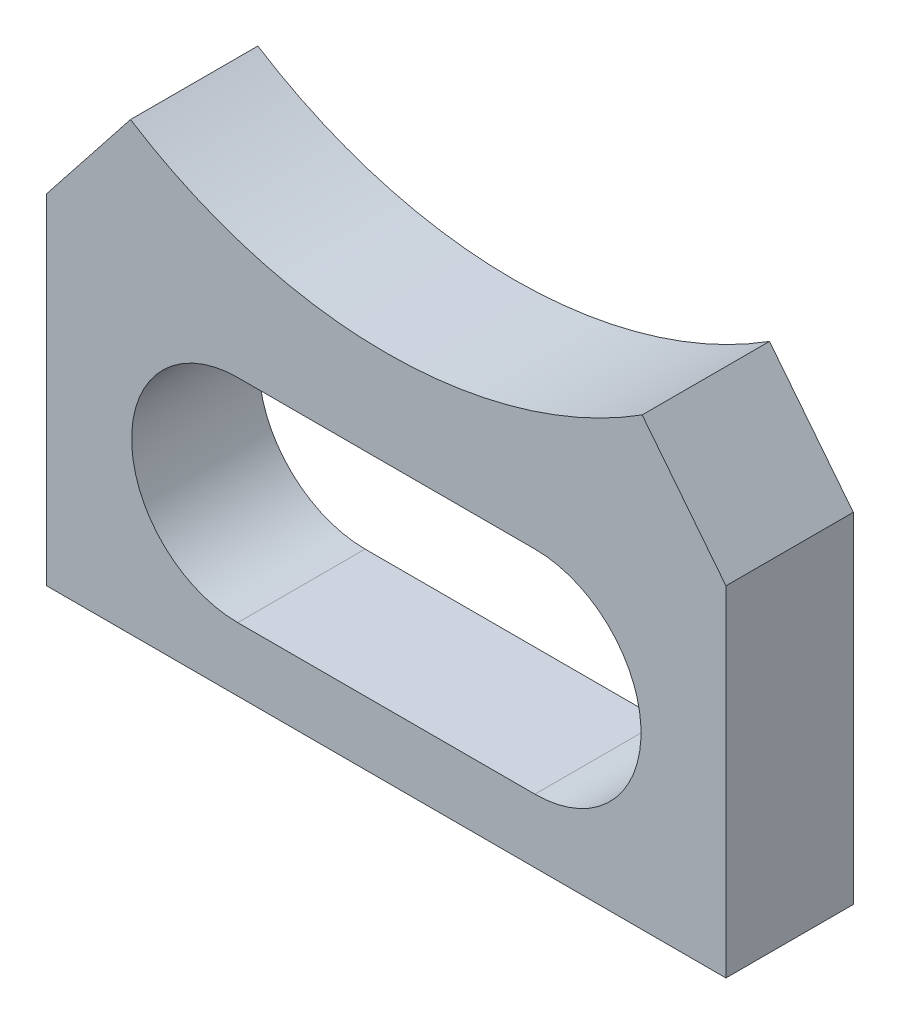
SolidWorks part; units mm, degrees
ref_plane "Plan de face" through (0, 0, 0) normal (0, 0, 1) x (1, 0, 0)
ref_plane "Plan de dessus" through (0, 0, 0) normal (0, 1, 0) x (1, 0, 0)
ref_plane "Plan de droite" through (0, 0, 0) normal (1, 0, 0) x (0, 0, -1)
sketch "Esquisse1" plane through (0, 0, 0) normal (0, 0, 1) x (1, 0, 0)
  line L0 (-16, 0) -> (16, 0)
  line L1 (-16, 0) -> (-16, 16)
  line L2 (0, 21) -> (12.052, 21) construction
  line L3 (16, 16) -> (16, 0)
  line L4 (-16, 16) -> (-12.052, 21)
  line L6 (-12.052, 21) -> (-16, 21) construction
  line L7 (12.052, 21) -> (16, 21) construction
  line L8 (0, 74.4173) -> (0, 62.5) construction
  line L10 (16, 16) -> (12.052, 21)
  line L11 (0, 62.5) -> (0, 21) construction
  line L12 (0, 21) -> (0, -33.4261) construction
  line L13 (-12.052, 21) -> (0, 21) construction
  line L14 (-7, 8) -> (7, 8) construction
  line L15 (-7, 13) -> (7, 13)
  line L16 (-7, 3) -> (7, 3)
  arc A0 (-12.052, 21) -> (12.052, 21) centre (0, 40) ccw
  arc A1 (0, 62.5) -> (-12.052, 21) centre (0, 40) ccw construction
  arc A2 (12.052, 21) -> (0, 62.5) centre (0, 40) ccw construction
  arc A3 (-7, 13) -> (-7, 3) centre (-7, 8) ccw
  arc A4 (7, 3) -> (7, 13) centre (7, 8) ccw
  point P14 (0, 17.5)
  point P17 (0, 8)
  dimension "D2" = 45
  dimension "D8" = 5
  dimension "D1" = 32
  dimension "D3" = 16
  dimension "D4" = 21
  dimension "D5" = 17.5
  dimension "D6" = 9
  dimension "D7" = 8
extrude "Boss.-Extru.2" add sketch "Esquisse1" against normal blind 6
sketch "Esquisse2" plane through (16, 0, 0) normal (1, 0, 0) x (0, 0, -1)
  line L0 (6, 16) -> (0, 16) construction
  line L1 (0, 0) -> (0, 16) construction
  circle A0 centre (3, 11) radius 0.8
  circle A1 centre (3, 4) radius 0.8
  point P7 (0, 0)
  point P10 (3, 11)
  point P11 (3, 4)
  point P12 (0, 0)
  dimension "D4" = 1.6
  dimension "D5" = 1.6
  dimension "D1" = 5
  dimension "D2" = 7
  dimension "D3" = 3
  dimension "D6" = 3
sketch "Esquisse3" plane through (-16, 0, 0) normal (-1, 0, 0) x (0, 0, 1)
  circle A0 centre (-3, 11) radius 0.8
  circle A1 centre (-3, 4) radius 0.8
  point P4 (0, 0)
  point P6 (0, 0)
  point P8 (-3.6361, 11)
  point P9 (0, 0)
  point P10 (0, 0)
  dimension "D1" = 1.6
  dimension "D2" = 1.6
